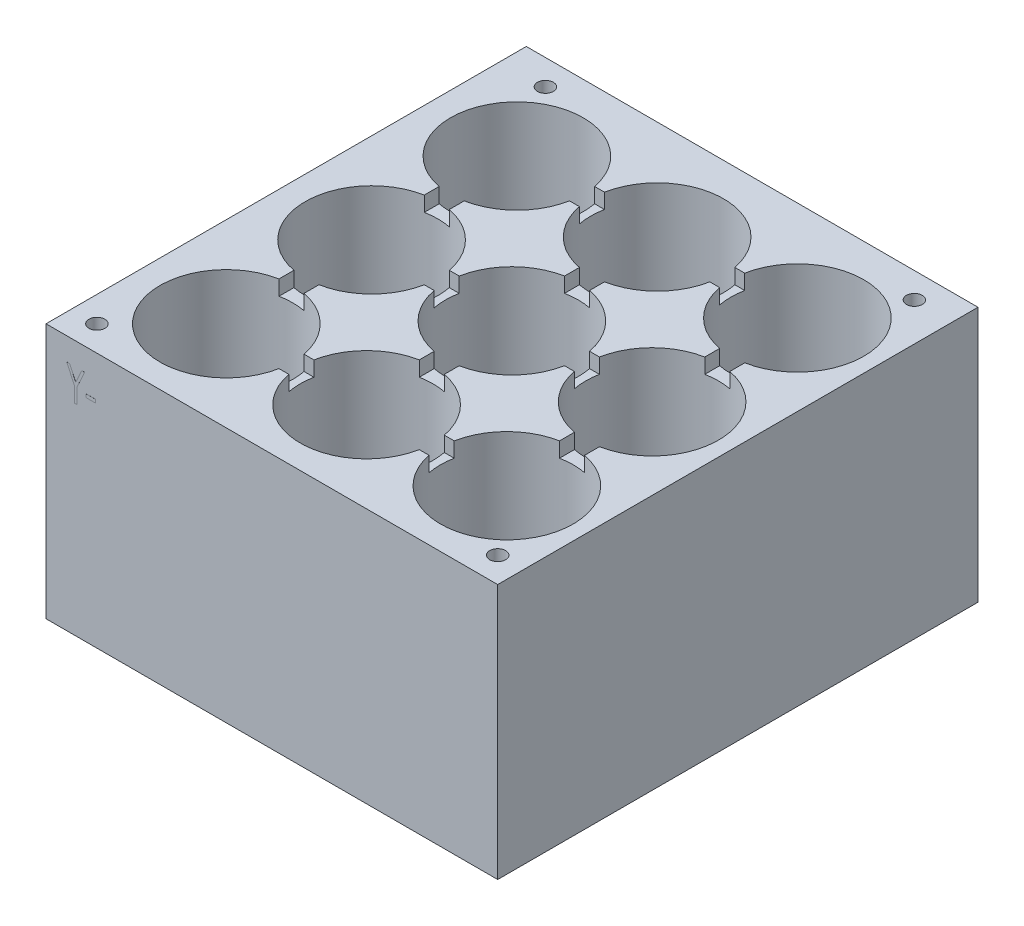
SolidWorks part; units mm, degrees
ref_plane "Front" through (0, 0, 0) normal (0, 0, 1) x (1, 0, 0)
ref_plane "Top" through (0, 0, 0) normal (0, 1, 0) x (1, 0, 0)
ref_plane "Right" through (0, 0, 0) normal (1, 0, 0) x (0, 0, -1)
sketch "Sketch1" plane through (0, 0, 0) normal (0, 1, 0) x (1, 0, 0)
  line L1 (-45.085, -47.9425) -> (45.085, -47.9425)
  line L2 (-45.085, -47.9425) -> (-45.085, 47.9425)
  line L3 (-45.085, 47.9425) -> (45.085, 47.9425)
  line L4 (45.085, -47.9425) -> (45.085, 47.9425)
  line L5 (-45.085, -47.9425) -> (45.085, 47.9425) construction
  line L6 (-45.085, 47.9425) -> (45.085, -47.9425) construction
  point P0 (0, 0)
  dimension "D1" = 95.885
  dimension "D2" = 90.17
extrude "Boss-Extrude1" add sketch "Sketch1" along normal blind 51
sketch "Sketch2" plane through (0, 51, 0) normal (0, 1, 0) x (1, 0, 0)
  line L0 (-45.085, -47.9425) -> (45.085, -47.9425) construction
  line L1 (-45.085, 47.9425) -> (-45.085, -47.9425) construction
  circle A0 centre (-36.195, 42.8625) radius 1.5875
  circle A1 centre (37.465, 42.8625) radius 1.5875
  circle A2 centre (-40.005, -42.8625) radius 1.5875
  circle A3 centre (40.005, -42.8625) radius 1.5875
  dimension "D1" = 3.175
  dimension "D2" = 80.01
  dimension "D3" = 3.81
  dimension "D4" = 85.725
  dimension "D5" = 73.66
  dimension "D6" = 5.08
  dimension "D7" = 5.08
extrude "Cut-Extrude1" cut sketch "Sketch2" against normal blind 51
sketch "Sketch3" plane through (0, 51, 0) normal (0, 1, 0) x (1, 0, 0)
  line L0 (-45.085, -47.9425) -> (45.085, -47.9425) construction
  line L1 (-45.085, 47.9425) -> (-45.085, -47.9425) construction
  circle A0 centre (-27.085, -29.9425) radius 13.25
  dimension "D1" = 26.5
  dimension "D2" = 18
  dimension "D3" = 18
extrude "Cut-Extrude2" cut sketch "Sketch3" against normal blind 51
pattern_linear "LPattern1" count 3 spacing 29 along (0, 0, -1) of "Cut-Extrude2"
pattern_linear "LPattern2" count 3 spacing 28 along (1, 0, 0) of "LPattern1", "Cut-Extrude2"
sketch "Sketch4" plane through (0, 0, 47.9425) normal (0, 0, 1) x (1, 0, 0)
  text T0 "Y- " font "Century Gothic" height 6.35
extrude "Boss-Extrude2" add sketch "Sketch4" along normal blind 0.01
sketch "Sketch6" plane through (0, 51, 0) normal (0, 1, 0) x (1, 0, 0)
  line L0 (-45.085, 47.9425) -> (-45.085, -47.9425) construction
  line L1 (-24.585, -20.4425) -> (-29.585, -20.4425)
  line L2 (-24.585, -20.4425) -> (-24.585, -10.4425)
  line L3 (-24.585, -10.4425) -> (-29.585, -10.4425)
  line L4 (-29.585, -20.4425) -> (-29.585, -10.4425)
  line L5 (-24.585, -20.4425) -> (-29.585, -10.4425) construction
  line L6 (-24.585, -10.4425) -> (-29.585, -20.4425) construction
  line L7 (-45.085, -47.9425) -> (45.085, -47.9425) construction
  point P0 (-27.085, -15.4425)
  dimension "D1" = 18
  dimension "D2" = 32.5
  dimension "D3" = 5
  dimension "D4" = 10
extrude "Cut-Extrude3" cut sketch "Sketch6" against normal blind 3
pattern_linear "LPattern3" count 2 spacing 29 along (0, 0, -1) of "Cut-Extrude3"
pattern_linear "LPattern4" count 3 spacing 28 along (1, 0, 0) of "LPattern3", "Cut-Extrude3"
sketch "Sketch7" plane through (0, 51, 0) normal (0, 1, 0) x (1, 0, 0)
  line L0 (-45.085, -47.9425) -> (45.085, -47.9425) construction
  line L1 (-17.2495, -27.4425) -> (-8.9205, -27.4425)
  line L2 (-17.2495, -27.4425) -> (-17.2495, -32.4425)
  line L3 (-17.2495, -32.4425) -> (-8.9205, -32.4425)
  line L4 (-8.9205, -27.4425) -> (-8.9205, -32.4425)
  line L5 (-17.2495, -27.4425) -> (-8.9205, -32.4425) construction
  line L6 (-17.2495, -32.4425) -> (-8.9205, -27.4425) construction
  line L7 (-45.085, 47.9425) -> (-45.085, -47.9425) construction
  point P0 (-13.085, -29.9425)
  dimension "D1" = 18
  dimension "D2" = 32
  dimension "D3" = 5
extrude "Cut-Extrude4" cut sketch "Sketch7" against normal blind 3
pattern_linear "LPattern5" count 2 spacing 28 along (1, 0, 0) of "Cut-Extrude4"
pattern_linear "LPattern6" count 3 spacing 29 along (0, 0, -1) of "LPattern5", "Cut-Extrude4"
ref_plane "Plane1" through (0, 25.5, 0) normal (0, 1, 0) x (1, 0, 0)
mirror "Mirror2" about plane through (0, 25.5, 0) normal (0, 1, 0) of "LPattern3", "LPattern4", "LPattern5", "LPattern6", "Cut-Extrude3", "Cut-Extrude4"
